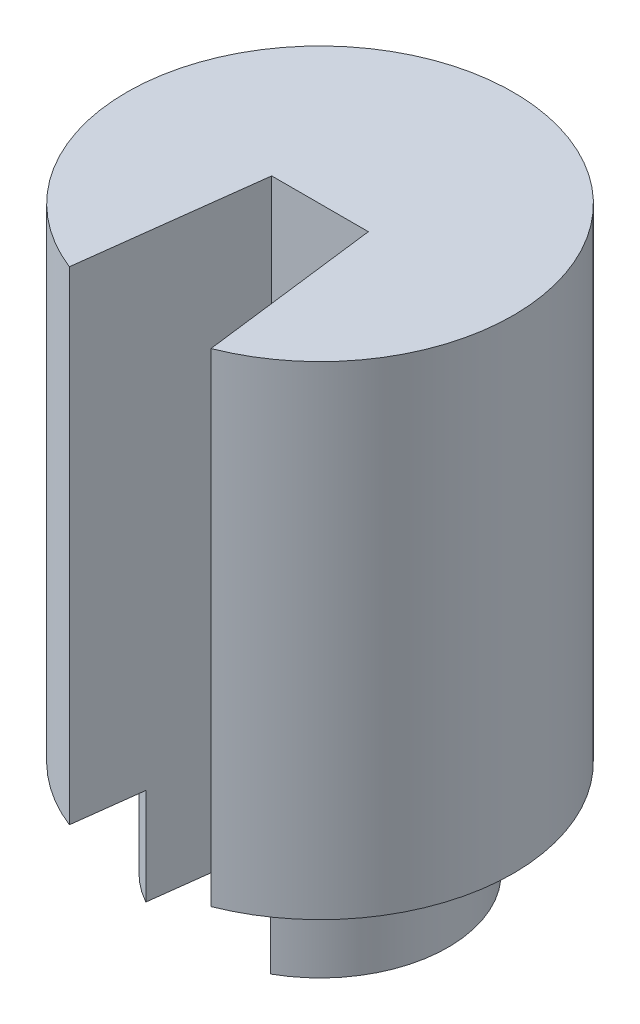
SolidWorks part; units mm, degrees
ref_plane "Front Plane" through (0, 0, 0) normal (0, 0, 1) x (1, 0, 0)
ref_plane "Top Plane" through (0, 0, 0) normal (0, 1, 0) x (1, 0, 0)
ref_plane "Right Plane" through (0, 0, 0) normal (1, 0, 0) x (0, 0, -1)
sketch "Sketch2" plane through (0, 0, 0) normal (0, 1, 0) x (1, 0, 0)
  circle A0 centre (0, 0) radius 2.65
  dimension "D1" = 5.3
extrude "Boss-Extrude1" add sketch "Sketch2" along normal blind 2
sketch "Sketch3" plane through (0, 2, 0) normal (0, 1, 0) x (1, 0, 0)
  circle A0 centre (0, 0) radius 4
  dimension "D1" = 8
extrude "Boss-Extrude2" add sketch "Sketch3" along normal blind 10
ref_plane "Plane1" through (0, 0, 4) normal (0, 0, 1) x (1, 0, 0)
sketch "Sketch4" plane through (0, 0, 4) normal (0, 0, 1) x (1, 0, 0)
  line L1 (-1.5, -12.3992) -> (1.5, -12.3992)
  line L2 (-1.5, -12.3992) -> (-1.5, 12.3992)
  line L3 (-1.5, 12.3992) -> (1.5, 12.3992)
  line L4 (1.5, -12.3992) -> (1.5, 12.3992)
  line L5 (-1.5, -12.3992) -> (1.5, 12.3992) construction
  line L6 (-1.5, 12.3992) -> (1.5, -12.3992) construction
  point P0 (0, 0)
  dimension "D1" = 3
sketch "Sketch5" plane through (0, 0, 0) normal (0, 0, 1) x (1, 0, 0)
  line L1 (-1, -12.2148) -> (1, -12.2148)
  line L2 (-1, -12.2148) -> (-1, 12.2148)
  line L3 (-1, 12.2148) -> (1, 12.2148)
  line L4 (1, -12.2148) -> (1, 12.2148)
  line L5 (-1, -12.2148) -> (1, 12.2148) construction
  line L6 (-1, 12.2148) -> (1, -12.2148) construction
  point P0 (0, 0)
  dimension "D1" = 2
loft "Cut-Loft1" cut profiles "Sketch4", "Sketch5"
